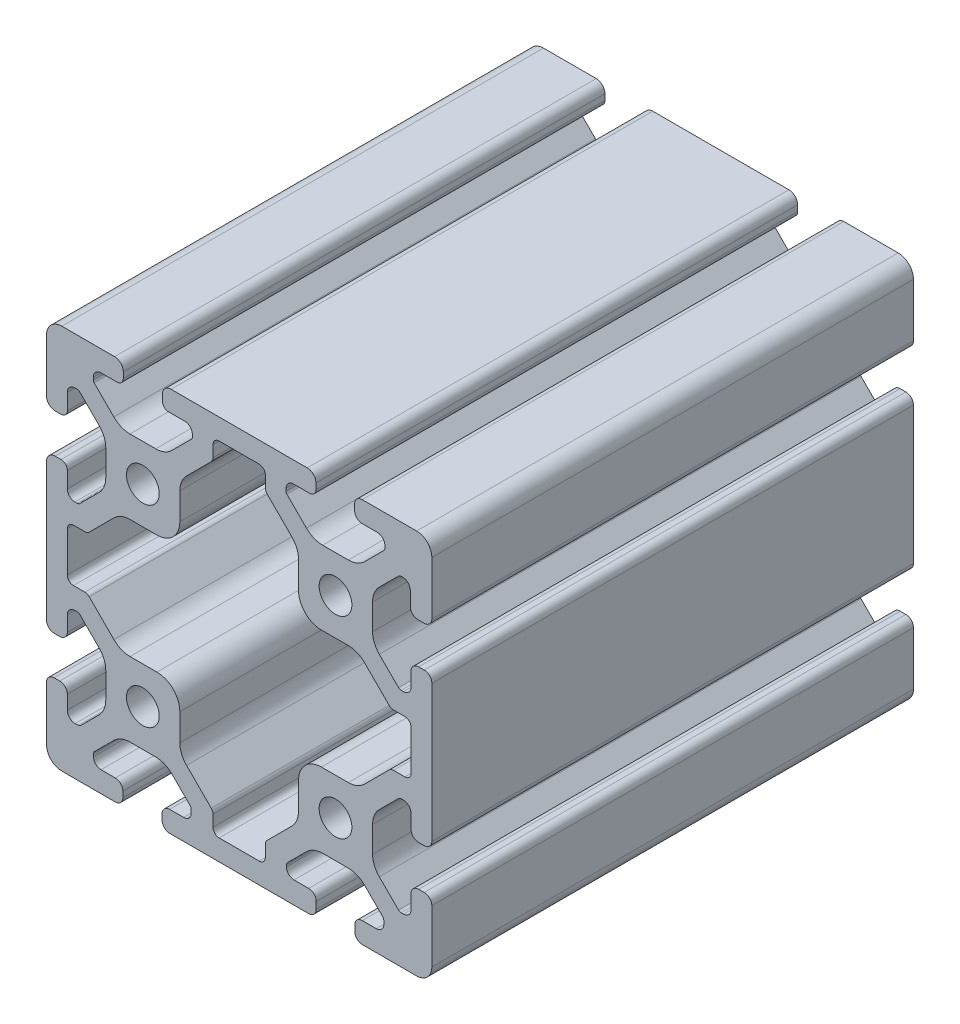
SolidWorks part; units mm, degrees
material "6061 Alloy"
ref_plane "Front Plane" through (0, 0, 0) normal (0, 0, 1) x (1, 0, 0)
ref_plane "Top Plane" through (0, 0, 0) normal (0, 1, 0) x (1, 0, 0)
ref_plane "Right Plane" through (0, 0, 0) normal (1, 0, 0) x (0, 0, -1)
sketch "Sketch1" plane through (0, 0, 0) normal (0, 0, 1) x (1, 0, 0)
  line L0 (0, -40) -> (0, 40) construction
  line L1 (0, 0) -> (-43.5804, 43.5804) construction
  line L2 (-20, 20) -> (-47.7323, 20) construction
  line L3 (-20, 20) -> (3.796, 43.796) construction
  line L4 (-20, 20) -> (-20, 43.5758) construction
  line L5 (-20, -27.7) -> (-20, -47.5576) construction
  line L7 (-36.8718, 24) -> (-28.8718, 24) construction
  line L8 (-36.8718, 24) -> (-36.8718, 16) construction
  line L9 (-36.8718, 16) -> (-28.8718, 16) construction
  line L10 (-28.8718, 24) -> (-28.8718, 16) construction
  line L11 (-36.8718, 24) -> (-28.8718, 16) construction
  line L12 (-36.8718, 16) -> (-28.8718, 24) construction
  line L131 (29.0912, 26.0365) -> (33.0827, 30.028)
  line L132 (27.7, 17.3222) -> (27.7, 22.6778)
  line L133 (29.0912, 13.9635) -> (33.0827, 9.972)
  line L134 (33.6201, 9.7494) -> (34.11, 9.7494)
  line L135 (35.68, 11.3194) -> (35.68, 14.2221)
  line L136 (37.25, 15.7921) -> (38.43, 15.7921)
  line L137 (40, 14.2221) -> (40, 7.0214)
  line L138 (40, 7.0214) -> (40, -7.0214)
  line L139 (40, -7.0214) -> (40, -14.2221)
  line L140 (38.43, -15.7921) -> (37.25, -15.7921)
  line L141 (35.68, -14.2221) -> (35.68, -11.3194)
  line L142 (33.6201, -9.7494) -> (34.11, -9.7494)
  line L143 (29.0912, -13.9635) -> (33.0827, -9.972)
  line L144 (27.7, -22.6778) -> (27.7, -17.3222)
  line L145 (29.0912, -26.0365) -> (33.0827, -30.028)
  line L146 (33.6201, -30.2506) -> (34.11, -30.2506)
  line L147 (35.68, -28.6806) -> (35.68, -25.7779)
  line L148 (37.25, -24.2079) -> (38.43, -24.2079)
  line L149 (40, -25.7779) -> (40, -33.0259)
  line L150 (40, -33.0259) -> (40, -36.83)
  line L151 (36.83, -40) -> (32.9998, -40)
  line L152 (32.9998, -40) -> (25.5696, -40)
  line L153 (23.9996, -38.43) -> (23.9996, -37.25)
  line L154 (25.5696, -35.68) -> (28.4723, -35.68)
  line L155 (30.0413, -34.0552) -> (30.0171, -33.3605)
  line L156 (29.7949, -32.8496) -> (26.0365, -29.0912)
  line L157 (17.3222, -27.7) -> (22.6778, -27.7)
  line L158 (10.035, -33.0197) -> (13.9635, -29.0912)
  line L159 (9.8124, -33.8926) -> (9.8124, -33.5571)
  line L160 (11.3824, -35.4626) -> (14.4246, -35.4626)
  line L161 (15.9946, -37.0326) -> (15.9946, -38.43)
  line L162 (14.4246, -40) -> (6.9987, -40)
  line L163 (6.9987, -40) -> (-6.9987, -40)
  line L164 (-6.9987, -40) -> (-14.4292, -40)
  line L165 (-15.9992, -38.43) -> (-15.9992, -37.25)
  line L166 (-14.4292, -35.68) -> (-11.5265, -35.68)
  line L167 (-9.9574, -34.0552) -> (-9.9816, -33.3618)
  line L168 (-10.2038, -32.8509) -> (-13.9635, -29.0912)
  line L169 (-22.6778, -27.7) -> (-17.3222, -27.7)
  line L170 (-30.028, -33.0827) -> (-26.0365, -29.0912)
  line L171 (-30.2506, -34.11) -> (-30.2506, -33.6201)
  line L172 (-28.6806, -35.68) -> (-25.7231, -35.68)
  line L173 (-24.1531, -37.25) -> (-24.1531, -38.43)
  line L174 (-25.7231, -40) -> (-33, -40)
  line L175 (-33, -40) -> (-36.83, -40)
  line L176 (-40, -36.83) -> (-40, -33.0191)
  line L177 (-40, -33.0191) -> (-40, -25.591)
  line L178 (-38.43, -24.021) -> (-37.25, -24.021)
  line L179 (-35.68, -28.4937) -> (-35.68, -25.591)
  line L180 (-34.0552, -30.0627) -> (-33.3827, -30.0392)
  line L181 (-32.8718, -29.8171) -> (-29.0912, -26.0365)
  line L182 (-27.7, -22.6778) -> (-27.7, -17.3222)
  line L183 (-29.0912, -13.9635) -> (-33.0827, -9.972)
  line L184 (-34.11, -9.7494) -> (-33.6201, -9.7494)
  line L185 (-35.68, -11.3194) -> (-35.68, -14.4473)
  line L186 (-38.43, -16.0173) -> (-37.25, -16.0173)
  line L187 (-40, -14.4473) -> (-40, -7.0169)
  line L188 (-40, -7.0169) -> (-40, 7.0169)
  line L189 (-40, 7.0169) -> (-40, 14.1348)
  line L190 (-38.1948, 15.94) -> (-36.9772, 15.94)
  line L191 (-35.68, 11.3194) -> (-35.68, 14.6428)
  line L192 (-34.11, 9.7494) -> (-33.6201, 9.7494)
  line L193 (-33.0827, 9.972) -> (-29.0912, 13.9635)
  line L194 (-27.7, 17.3222) -> (-27.7, 22.6778)
  line L195 (-29.0912, 26.0365) -> (-33.0827, 30.028)
  line L196 (-34.11, 30.2506) -> (-33.6201, 30.2506)
  line L197 (-35.68, 28.6806) -> (-35.68, 25.3572)
  line L198 (-38.1948, 24.06) -> (-36.9772, 24.06)
  line L199 (-40, 25.8652) -> (-40, 33.3181)
  line L200 (-40, 33.3181) -> (-40, 36.83)
  line L201 (-36.83, 40) -> (-33.0314, 40)
  line L202 (-33.0314, 40) -> (-25.8652, 40)
  line L203 (-24.06, 36.9772) -> (-24.06, 38.1948)
  line L204 (-25.3572, 35.68) -> (-28.7018, 35.68)
  line L205 (-30.285, 33.6069) -> (-30.285, 34.0968)
  line L206 (-30.0961, 33.1508) -> (-26.0365, 29.0912)
  line L207 (-22.6778, 27.7) -> (-17.3222, 27.7)
  line L208 (-13.9635, 29.0912) -> (-9.9039, 33.1508)
  line L209 (-9.715, 33.6069) -> (-9.715, 34.0968)
  line L210 (-14.6428, 35.68) -> (-11.2982, 35.68)
  line L211 (-15.94, 36.9772) -> (-15.94, 38.1948)
  line L212 (-14.1348, 40) -> (-6.9844, 40)
  line L213 (-6.9844, 40) -> (6.9844, 40)
  line L214 (6.9844, 40) -> (14.1348, 40)
  line L215 (15.94, 36.9772) -> (15.94, 38.1948)
  line L216 (14.6428, 35.68) -> (11.2982, 35.68)
  line L217 (9.715, 33.6069) -> (9.715, 34.0968)
  line L218 (9.9039, 33.1508) -> (13.9635, 29.0912)
  line L219 (17.3222, 27.7) -> (22.6778, 27.7)
  line L220 (26.0365, 29.0912) -> (30.028, 33.0827)
  line L221 (30.2506, 33.6201) -> (30.2506, 34.11)
  line L222 (25.5409, 35.679) -> (28.6258, 35.679)
  line L223 (23.9709, 37.249) -> (23.9709, 38.43)
  line L224 (25.5409, 40) -> (36.83, 40)
  line L226 (40, 36.83) -> (40, 32.9339)
  line L227 (40, 32.9339) -> (40, 25.7779)
  line L228 (38.43, 24.2079) -> (37.0956, 24.2079)
  line L229 (35.5256, 25.7779) -> (35.5256, 28.6806)
  line L230 (33.6201, 30.2506) -> (33.9556, 30.2506)
  line L231 (17.07, 12.32) -> (22.6578, 12.32)
  line L232 (26.0165, 10.9288) -> (31.1439, 5.8014)
  line L233 (32.0419, 5.4294) -> (34.41, 5.4294)
  line L234 (35.68, -4.1594) -> (35.68, 4.1594)
  line L235 (32.0419, -5.4294) -> (34.41, -5.4294)
  line L236 (26.0165, -10.9288) -> (31.1439, -5.8014)
  line L237 (17.07, -12.32) -> (22.6578, -12.32)
  line L238 (12.32, -22.6578) -> (12.32, -17.07)
  line L239 (5.8014, -31.1439) -> (10.9288, -26.0165)
  line L240 (5.4294, -34.41) -> (5.4294, -32.0419)
  line L241 (-4.1594, -35.68) -> (4.1594, -35.68)
  line L242 (-5.4294, -34.41) -> (-5.4294, -32.0419)
  line L243 (-5.8014, -31.1439) -> (-10.9288, -26.0165)
  line L244 (-12.32, -22.6578) -> (-12.32, -17.07)
  line L245 (-22.6578, -12.32) -> (-17.07, -12.32)
  line L246 (-26.0165, -10.9288) -> (-31.1439, -5.8014)
  line L247 (-34.41, -5.4294) -> (-32.0419, -5.4294)
  line L248 (-35.68, -4.1594) -> (-35.68, 4.1594)
  line L249 (-34.41, 5.4294) -> (-32.0419, 5.4294)
  line L250 (-31.1439, 5.8014) -> (-26.0165, 10.9288)
  line L251 (-22.6578, 12.32) -> (-17.07, 12.32)
  line L252 (-12.32, 17.07) -> (-12.32, 22.6578)
  line L253 (-10.9288, 26.0165) -> (-5.8014, 31.1439)
  line L254 (-5.4294, 32.0419) -> (-5.4294, 34.41)
  line L255 (-4.1594, 35.68) -> (4.1594, 35.68)
  line L256 (5.4294, 32.0419) -> (5.4294, 34.41)
  line L257 (5.8014, 31.1439) -> (10.9288, 26.0165)
  line L258 (12.32, 17.07) -> (12.32, 22.6578)
  line L260 (-40, 0) -> (40, 0) construction
  circle A0 centre (-32.8718, 20) radius 4 construction
  circle A116 centre (-20, 20) radius 3.4
  circle A117 centre (20, 20) radius 3.4
  circle A118 centre (20, -20) radius 3.4
  circle A119 centre (-20, -20) radius 3.4
  arc A120 (29.0912, 26.0365) -> (27.7, 22.6778) centre (32.45, 22.6778) ccw
  arc A121 (27.7, 17.3222) -> (29.0912, 13.9635) centre (32.45, 17.3222) ccw
  arc A122 (33.0827, 9.972) -> (33.6201, 9.7494) centre (33.6201, 10.5094) ccw
  arc A123 (34.11, 9.7494) -> (35.68, 11.3194) centre (34.11, 11.3194) ccw
  arc A124 (37.25, 15.7921) -> (35.68, 14.2221) centre (37.25, 14.2221) ccw
  arc A125 (40, 14.2221) -> (38.43, 15.7921) centre (38.43, 14.2221) ccw
  arc A126 (38.43, -15.7921) -> (40, -14.2221) centre (38.43, -14.2221) ccw
  arc A127 (35.68, -14.2221) -> (37.25, -15.7921) centre (37.25, -14.2221) ccw
  arc A128 (35.68, -11.3194) -> (34.11, -9.7494) centre (34.11, -11.3194) ccw
  arc A129 (33.6201, -9.7494) -> (33.0827, -9.972) centre (33.6201, -10.5094) ccw
  arc A130 (29.0912, -13.9635) -> (27.7, -17.3222) centre (32.45, -17.3222) ccw
  arc A131 (27.7, -22.6778) -> (29.0912, -26.0365) centre (32.45, -22.6778) ccw
  arc A132 (33.0827, -30.028) -> (33.6201, -30.2506) centre (33.6201, -29.4906) ccw
  arc A133 (34.11, -30.2506) -> (35.68, -28.6806) centre (34.11, -28.6806) ccw
  arc A134 (37.25, -24.2079) -> (35.68, -25.7779) centre (37.25, -25.7779) ccw
  arc A135 (40, -25.7779) -> (38.43, -24.2079) centre (38.43, -25.7779) ccw
  arc A136 (36.83, -40) -> (40, -36.83) centre (36.83, -36.83) ccw
  arc A137 (23.9996, -38.43) -> (25.5696, -40) centre (25.5696, -38.43) ccw
  arc A138 (25.5696, -35.68) -> (23.9996, -37.25) centre (25.5696, -37.25) ccw
  arc A139 (28.4723, -35.68) -> (30.0413, -34.0552) centre (28.4723, -34.11) ccw
  arc A140 (30.0171, -33.3605) -> (29.7949, -32.8496) centre (29.2575, -33.387) ccw
  arc A141 (26.0365, -29.0912) -> (22.6778, -27.7) centre (22.6778, -32.45) ccw
  arc A142 (17.3222, -27.7) -> (13.9635, -29.0912) centre (17.3222, -32.45) ccw
  arc A143 (10.035, -33.0197) -> (9.8124, -33.5571) centre (10.5724, -33.5571) ccw
  arc A144 (9.8124, -33.8926) -> (11.3824, -35.4626) centre (11.3824, -33.8926) ccw
  arc A145 (15.9946, -37.0326) -> (14.4246, -35.4626) centre (14.4246, -37.0326) ccw
  arc A146 (14.4246, -40) -> (15.9946, -38.43) centre (14.4246, -38.43) ccw
  arc A147 (-15.9992, -38.43) -> (-14.4292, -40) centre (-14.4292, -38.43) ccw
  arc A148 (-14.4292, -35.68) -> (-15.9992, -37.25) centre (-14.4292, -37.25) ccw
  arc A149 (-11.5265, -35.68) -> (-9.9574, -34.0552) centre (-11.5265, -34.11) ccw
  arc A150 (-9.9816, -33.3618) -> (-10.2038, -32.8509) centre (-10.7412, -33.3883) ccw
  arc A151 (-13.9635, -29.0912) -> (-17.3222, -27.7) centre (-17.3222, -32.45) ccw
  arc A152 (-22.6778, -27.7) -> (-26.0365, -29.0912) centre (-22.6778, -32.45) ccw
  arc A153 (-30.028, -33.0827) -> (-30.2506, -33.6201) centre (-29.4906, -33.6201) ccw
  arc A154 (-30.2506, -34.11) -> (-28.6806, -35.68) centre (-28.6806, -34.11) ccw
  arc A155 (-24.1531, -37.25) -> (-25.7231, -35.68) centre (-25.7231, -37.25) ccw
  arc A156 (-25.7231, -40) -> (-24.1531, -38.43) centre (-25.7231, -38.43) ccw
  arc A157 (-40, -36.83) -> (-36.83, -40) centre (-36.83, -36.83) ccw
  arc A158 (-38.43, -24.021) -> (-40, -25.591) centre (-38.43, -25.591) ccw
  arc A159 (-35.68, -25.591) -> (-37.25, -24.021) centre (-37.25, -25.591) ccw
  arc A160 (-35.68, -28.4937) -> (-34.0552, -30.0627) centre (-34.11, -28.4937) ccw
  arc A161 (-33.3827, -30.0392) -> (-32.8718, -29.8171) centre (-33.4092, -29.2797) ccw
  arc A162 (-29.0912, -26.0365) -> (-27.7, -22.6778) centre (-32.45, -22.6778) ccw
  arc A163 (-27.7, -17.3222) -> (-29.0912, -13.9635) centre (-32.45, -17.3222) ccw
  arc A164 (-33.0827, -9.972) -> (-33.6201, -9.7494) centre (-33.6201, -10.5094) ccw
  arc A165 (-34.11, -9.7494) -> (-35.68, -11.3194) centre (-34.11, -11.3194) ccw
  arc A166 (-37.25, -16.0173) -> (-35.68, -14.4473) centre (-37.25, -14.4473) ccw
  arc A167 (-40, -14.4473) -> (-38.43, -16.0173) centre (-38.43, -14.4473) ccw
  arc A168 (-38.1948, 15.94) -> (-40, 14.1348) centre (-38.1948, 14.1348) ccw
  arc A169 (-35.68, 14.6428) -> (-36.9772, 15.94) centre (-36.9772, 14.6428) ccw
  arc A170 (-35.68, 11.3194) -> (-34.11, 9.7494) centre (-34.11, 11.3194) ccw
  arc A171 (-33.6201, 9.7494) -> (-33.0827, 9.972) centre (-33.6201, 10.5094) ccw
  arc A172 (-29.0912, 13.9635) -> (-27.7, 17.3222) centre (-32.45, 17.3222) ccw
  arc A173 (-27.7, 22.6778) -> (-29.0912, 26.0365) centre (-32.45, 22.6778) ccw
  arc A174 (-33.0827, 30.028) -> (-33.6201, 30.2506) centre (-33.6201, 29.4906) ccw
  arc A175 (-34.11, 30.2506) -> (-35.68, 28.6806) centre (-34.11, 28.6806) ccw
  arc A176 (-36.9772, 24.06) -> (-35.68, 25.3572) centre (-36.9772, 25.3572) ccw
  arc A177 (-40, 25.8652) -> (-38.1948, 24.06) centre (-38.1948, 25.8652) ccw
  arc A178 (-36.83, 40) -> (-40, 36.83) centre (-36.83, 36.83) ccw
  arc A179 (-24.06, 38.1948) -> (-25.8652, 40) centre (-25.8652, 38.1948) ccw
  arc A180 (-25.3572, 35.68) -> (-24.06, 36.9772) centre (-25.3572, 36.9772) ccw
  arc A181 (-28.7018, 35.68) -> (-30.285, 34.0968) centre (-28.7018, 34.0968) ccw
  arc A182 (-30.285, 33.6069) -> (-30.0961, 33.1508) centre (-29.6399, 33.6069) ccw
  arc A183 (-26.0365, 29.0912) -> (-22.6778, 27.7) centre (-22.6778, 32.45) ccw
  arc A184 (-17.3222, 27.7) -> (-13.9635, 29.0912) centre (-17.3222, 32.45) ccw
  arc A185 (-9.9039, 33.1508) -> (-9.715, 33.6069) centre (-10.3601, 33.6069) ccw
  arc A186 (-9.715, 34.0968) -> (-11.2982, 35.68) centre (-11.2982, 34.0968) ccw
  arc A187 (-15.94, 36.9772) -> (-14.6428, 35.68) centre (-14.6428, 36.9772) ccw
  arc A188 (-14.1348, 40) -> (-15.94, 38.1948) centre (-14.1348, 38.1948) ccw
  arc A189 (15.94, 38.1948) -> (14.1348, 40) centre (14.1348, 38.1948) ccw
  arc A190 (14.6428, 35.68) -> (15.94, 36.9772) centre (14.6428, 36.9772) ccw
  arc A191 (11.2982, 35.68) -> (9.715, 34.0968) centre (11.2982, 34.0968) ccw
  arc A192 (9.715, 33.6069) -> (9.9039, 33.1508) centre (10.3601, 33.6069) ccw
  arc A193 (13.9635, 29.0912) -> (17.3222, 27.7) centre (17.3222, 32.45) ccw
  arc A194 (22.6778, 27.7) -> (26.0365, 29.0912) centre (22.6778, 32.45) ccw
  arc A195 (30.028, 33.0827) -> (30.2506, 33.6201) centre (29.4906, 33.6201) ccw
  arc A196 (30.2506, 34.11) -> (28.6258, 35.679) centre (28.6806, 34.11) ccw
  arc A197 (23.9709, 37.249) -> (25.5409, 35.679) centre (25.5409, 37.249) ccw
  arc A198 (25.5409, 40) -> (23.9709, 38.43) centre (25.5409, 38.43) ccw
  arc A199 (40, 36.83) -> (36.83, 40) centre (36.83, 36.83) ccw
  arc A200 (38.43, 24.2079) -> (40, 25.7779) centre (38.43, 25.7779) ccw
  arc A201 (35.5256, 25.7779) -> (37.0956, 24.2079) centre (37.0956, 25.7779) ccw
  arc A202 (35.5256, 28.6806) -> (33.9556, 30.2506) centre (33.9556, 28.6806) ccw
  arc A203 (33.6201, 30.2506) -> (33.0827, 30.028) centre (33.6201, 29.4906) ccw
  arc A204 (26.0165, 10.9288) -> (22.6578, 12.32) centre (22.6578, 7.57) ccw
  arc A205 (31.1439, 5.8014) -> (32.0419, 5.4294) centre (32.0419, 6.6994) ccw
  arc A206 (35.68, 4.1594) -> (34.41, 5.4294) centre (34.41, 4.1594) ccw
  arc A207 (34.41, -5.4294) -> (35.68, -4.1594) centre (34.41, -4.1594) ccw
  arc A208 (32.0419, -5.4294) -> (31.1439, -5.8014) centre (32.0419, -6.6994) ccw
  arc A209 (22.6578, -12.32) -> (26.0165, -10.9288) centre (22.6578, -7.57) ccw
  arc A210 (17.07, -12.32) -> (12.32, -17.07) centre (17.07, -17.07) ccw
  arc A211 (10.9288, -26.0165) -> (12.32, -22.6578) centre (7.57, -22.6578) ccw
  arc A212 (5.8014, -31.1439) -> (5.4294, -32.0419) centre (6.6994, -32.0419) ccw
  arc A213 (4.1594, -35.68) -> (5.4294, -34.41) centre (4.1594, -34.41) ccw
  arc A214 (-5.4294, -34.41) -> (-4.1594, -35.68) centre (-4.1594, -34.41) ccw
  arc A215 (-5.4294, -32.0419) -> (-5.8014, -31.1439) centre (-6.6994, -32.0419) ccw
  arc A216 (-12.32, -22.6578) -> (-10.9288, -26.0165) centre (-7.57, -22.6578) ccw
  arc A217 (-12.32, -17.07) -> (-17.07, -12.32) centre (-17.07, -17.07) ccw
  arc A218 (-26.0165, -10.9288) -> (-22.6578, -12.32) centre (-22.6578, -7.57) ccw
  arc A219 (-31.1439, -5.8014) -> (-32.0419, -5.4294) centre (-32.0419, -6.6994) ccw
  arc A220 (-35.68, -4.1594) -> (-34.41, -5.4294) centre (-34.41, -4.1594) ccw
  arc A221 (-34.41, 5.4294) -> (-35.68, 4.1594) centre (-34.41, 4.1594) ccw
  arc A222 (-32.0419, 5.4294) -> (-31.1439, 5.8014) centre (-32.0419, 6.6994) ccw
  arc A223 (-22.6578, 12.32) -> (-26.0165, 10.9288) centre (-22.6578, 7.57) ccw
  arc A224 (-17.07, 12.32) -> (-12.32, 17.07) centre (-17.07, 17.07) ccw
  arc A225 (-10.9288, 26.0165) -> (-12.32, 22.6578) centre (-7.57, 22.6578) ccw
  arc A226 (-5.8014, 31.1439) -> (-5.4294, 32.0419) centre (-6.6994, 32.0419) ccw
  arc A227 (-4.1594, 35.68) -> (-5.4294, 34.41) centre (-4.1594, 34.41) ccw
  arc A228 (5.4294, 34.41) -> (4.1594, 35.68) centre (4.1594, 34.41) ccw
  arc A229 (5.4294, 32.0419) -> (5.8014, 31.1439) centre (6.6994, 32.0419) ccw
  arc A230 (12.32, 22.6578) -> (10.9288, 26.0165) centre (7.57, 22.6578) ccw
  arc A231 (12.32, 17.07) -> (17.07, 12.32) centre (17.07, 17.07) ccw
  point P9 (-32.8718, 20)
  dimension "D8" = 6.8
  dimension "D1" = 80
  dimension "D2" = 40
  dimension "D3" = 20
  dimension "D4" = 20.57
  dimension "D5" = 4.32
  dimension "D6" = 4.32
  dimension "D7" = 8.12
  dimension "D9" = 4.32
  dimension "D10" = 12.3
  dimension "D11" = 8
  dimension "D12" = 8
extrude "Extrude1" add sketch "Sketch1" against normal blind 100
